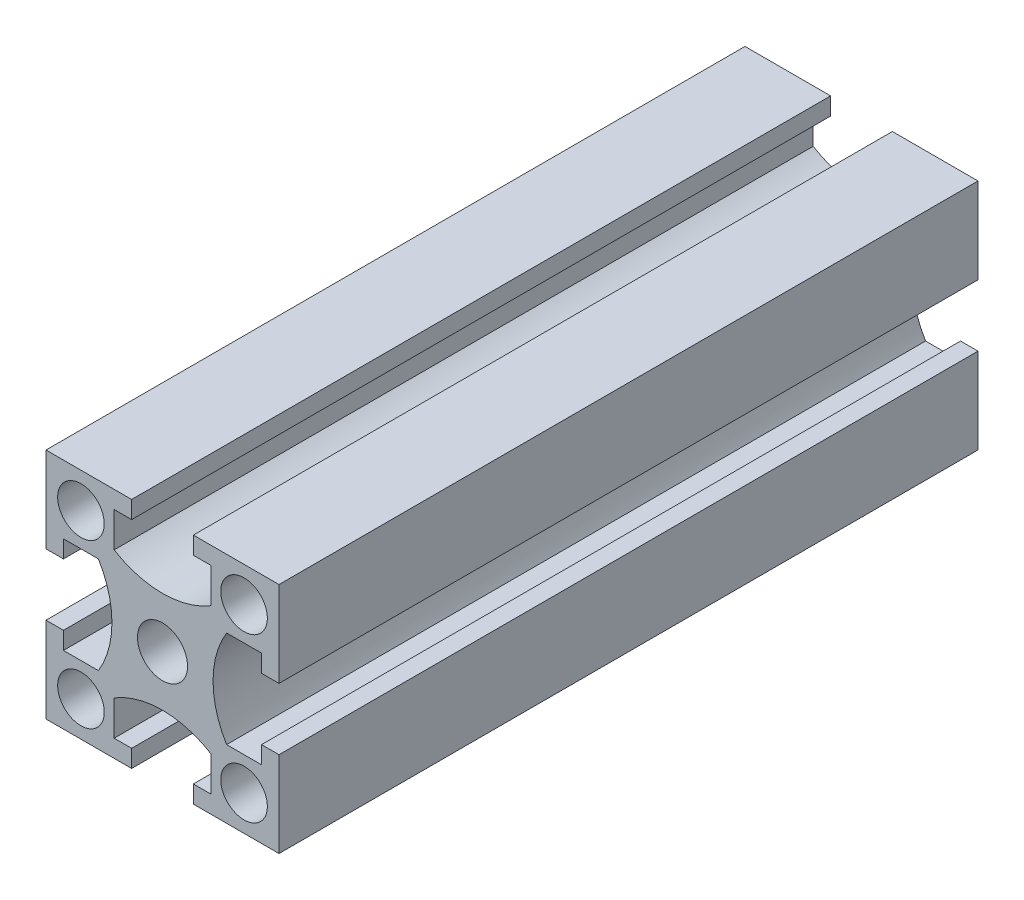
SolidWorks part; units mm, degrees
material "6061-T6 (SS)"
ref_plane "정면" through (0, 0, 0) normal (0, 0, 1) x (1, 0, 0)
ref_plane "윗면" through (0, 0, 0) normal (0, 1, 0) x (1, 0, 0)
ref_plane "우측면" through (0, 0, 0) normal (1, 0, 0) x (0, 0, -1)
sketch "스케치1" plane through (0, 0, 0) normal (0, 0, 1) x (1, 0, 0)
  line L1 (-10, 10) -> (10, 10)
  line L2 (-10, 10) -> (-10, -10)
  line L3 (-10, -10) -> (10, -10)
  line L4 (10, 10) -> (10, -10)
  line L5 (-10, 10) -> (10, -10) construction
  line L6 (-10, -10) -> (10, 10) construction
  point P0 (0, 0)
  dimension "D1" = 20
  dimension "D2" = 20
extrude "보스-돌출1" add sketch "스케치1" along normal blind 60
sketch "스케치2" plane through (0, 0, 60) normal (0, 0, 1) x (1, 0, 0)
  line L0 (-2.65, 10) -> (-2.65, 8.5)
  line L1 (10, 10) -> (-10, 10) construction
  line L2 (-2.65, 8.5) -> (-4.15, 8.5)
  line L3 (-4.15, 8.5) -> (-4.15, 5.5)
  line L4 (-2.65, 10) -> (2.65, 10)
  line L5 (2.65, 10) -> (2.65, 8.5)
  line L6 (2.65, 8.5) -> (4.15, 8.5)
  line L7 (4.15, 8.5) -> (4.15, 5.5)
  line L8 (10, 2.65) -> (8.5, 2.65)
  line L9 (8.5, 2.65) -> (8.5, 4.15)
  line L10 (8.5, 4.15) -> (5.5, 4.15)
  line L11 (10, 2.65) -> (10, -2.65)
  line L12 (10, -2.65) -> (8.5, -2.65)
  line L13 (8.5, -2.65) -> (8.5, -4.15)
  line L14 (8.5, -4.15) -> (5.5, -4.15)
  line L15 (2.65, -10) -> (2.65, -8.5)
  line L16 (2.65, -8.5) -> (4.15, -8.5)
  line L17 (4.15, -8.5) -> (4.15, -5.5)
  line L18 (2.65, -10) -> (-2.65, -10)
  line L19 (-2.65, -10) -> (-2.65, -8.5)
  line L20 (-2.65, -8.5) -> (-4.15, -8.5)
  line L21 (-4.15, -8.5) -> (-4.15, -5.5)
  line L22 (-10, -2.65) -> (-8.5, -2.65)
  line L23 (-8.5, -2.65) -> (-8.5, -4.15)
  line L24 (-8.5, -4.15) -> (-5.5, -4.15)
  line L25 (-10, -2.65) -> (-10, 2.65)
  line L26 (-10, 2.65) -> (-8.5, 2.65)
  line L27 (-8.5, 2.65) -> (-8.5, 4.15)
  line L28 (-8.5, 4.15) -> (-5.5, 4.15)
  arc A1 (-4.15, 5.5) -> (4.15, 5.5) centre (0, 12.3394) ccw
  arc A2 (5.5, 4.15) -> (5.5, -4.15) centre (12.3394, 0) ccw
  arc A3 (4.15, -5.5) -> (-4.15, -5.5) centre (0, -12.3394) ccw
  arc A4 (-5.5, -4.15) -> (-5.5, 4.15) centre (-12.3394, 0) ccw
  circle A5 centre (0, 0) radius 2.15
  circle A6 centre (-7, 7) radius 2
  circle A7 centre (7, 7) radius 2
  circle A8 centre (7, -7) radius 2
  circle A9 centre (-7, -7) radius 2
  point P4 (-2.65, 9.25)
  point P43 (0, 0)
  dimension "D2" = 1.5
  dimension "D8" = 4.3
  dimension "D9" = 4
  dimension "D10" = 4
  dimension "D11" = 4
  dimension "D12" = 4
  dimension "D21" = 8
  dimension "D1" = 5.3
  dimension "D3" = 8.3
  dimension "D4" = 4.15
  dimension "D5" = 2.65
  dimension "D6" = 4
  dimension "D7" = 3
  dimension "D13" = 14
  dimension "D14" = 7
  dimension "D15" = 7
  dimension "D16" = 7
  dimension "D17" = 14
  dimension "D18" = 7
  dimension "D19" = 7
  dimension "D20" = 7
extrude "컷-돌출1" cut sketch "스케치2" against normal blind 300
